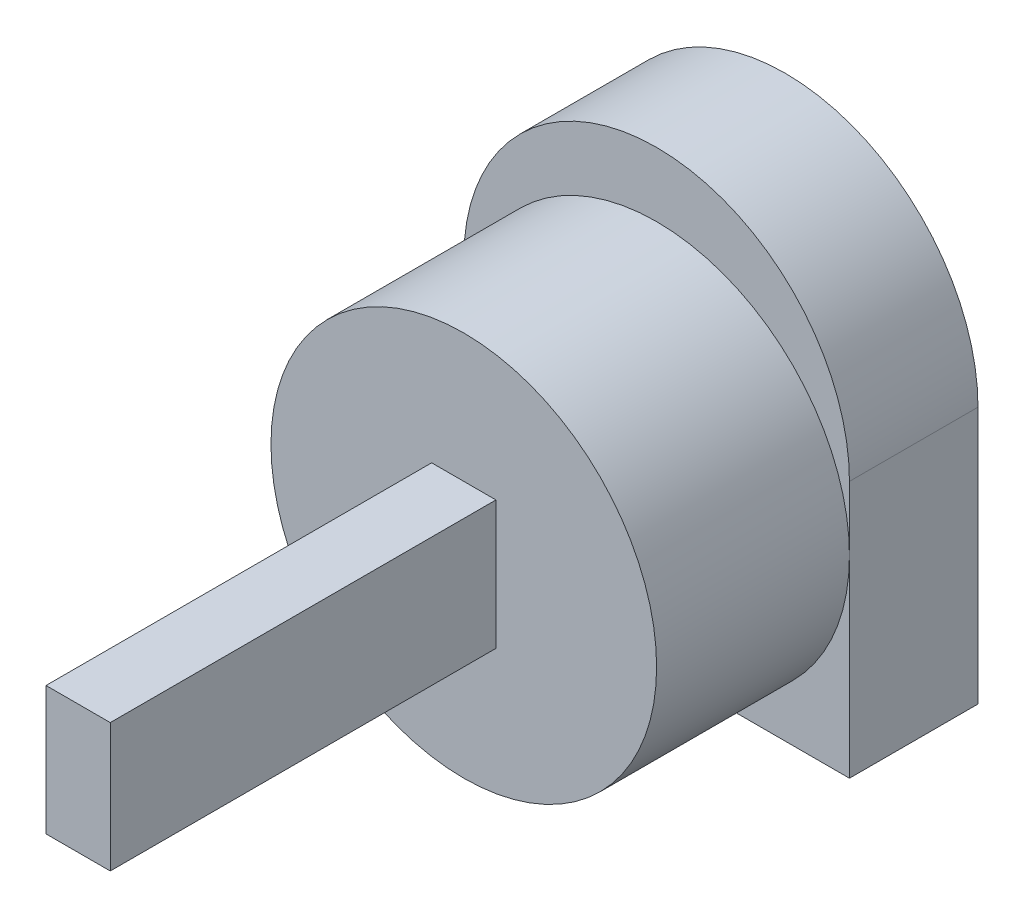
SolidWorks part; units mm, degrees
ref_plane "正面" through (0, 0, 0) normal (0, 0, 1) x (1, 0, 0)
ref_plane "平面" through (0, 0, 0) normal (0, 1, 0) x (1, 0, 0)
ref_plane "右側面" through (0, 0, 0) normal (1, 0, 0) x (0, 0, -1)
sketch "ｽｹｯﾁ1" plane through (0, 0, 0) normal (0, 0, 1) x (1, 0, 0)
  line L0 (0, 0) -> (30, 0)
  line L1 (30, 0) -> (30, 20)
  line L2 (0, 20) -> (0, 0)
  arc A0 (30, 20) -> (0, 20) centre (15, 20) ccw
  point P6 (0, 31.5615)
  dimension "D1" = 30
  dimension "D2" = 20
extrude "ﾎﾞｽ - 押し出し1" add sketch "ｽｹｯﾁ1" along normal blind 10
sketch "ｽｹｯﾁ2" plane through (0, 0, 10) normal (0, 0, 1) x (1, 0, 0)
  line L0 (0, 0) -> (30, 0) construction
  line L1 (30, 0) -> (30, 20) construction
  line L2 (0, 20) -> (0, 0) construction
  circle A0 centre (15, 15) radius 15
extrude "ﾎﾞｽ - 押し出し2" add sketch "ｽｹｯﾁ2" along normal blind 15
sketch "ｽｹｯﾁ3" plane through (0, 0, 25) normal (0, 0, 1) x (1, 0, 0)
  line L0 (17.5, 15) -> (12.5, 15) construction
  line L1 (12.5, 20) -> (17.5, 20)
  line L2 (12.5, 20) -> (12.5, 10)
  line L3 (12.5, 10) -> (17.5, 10)
  line L4 (17.5, 20) -> (17.5, 10)
  circle A0 centre (15, 15) radius 15 construction
  point P6 (15, 15)
  dimension "D1" = 5
  dimension "D2" = 10
extrude "ﾎﾞｽ - 押し出し3" add sketch "ｽｹｯﾁ3" along normal blind 30
